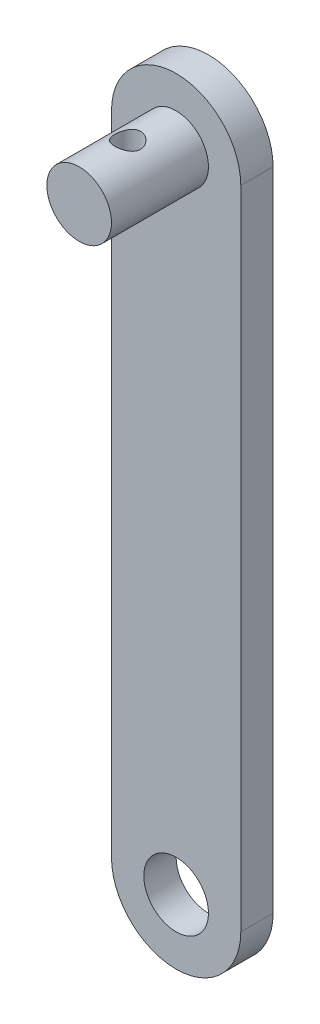
SolidWorks part; units mm, degrees
ref_plane "Front Plane" through (0, 0, 0) normal (0, 0, 1) x (1, 0, 0)
ref_plane "Top Plane" through (0, 0, 0) normal (0, 1, 0) x (1, 0, 0)
ref_plane "Right Plane" through (0, 0, 0) normal (1, 0, 0) x (0, 0, -1)
sketch "Sketch1" plane through (0, 0, 0) normal (0, 0, 1) x (1, 0, 0)
  line L0 (-12.7, -63.5) -> (-12.7, 63.5)
  line L1 (12.7, -63.5) -> (12.7, 63.5)
  line L2 (-22.7949, 0) -> (48.0321, 0) construction
  line L3 (-65.5814, 76.2) -> (65.5814, 76.2) construction
  arc A0 (-12.7, 63.5) -> (12.7, 63.5) centre (0, 63.5) cw
  circle A1 centre (0, 63.5) radius 6.35
  circle A2 centre (0, -63.5) radius 6.35
  arc A3 (-12.7, -63.5) -> (12.7, -63.5) centre (0, -63.5) ccw
  point P2 (-12.7, 0)
  point P13 (12.7, 0)
  point P15 (0, 76.2)
  dimension "D1" = 12.7
  dimension "D3" = 12.7
  dimension "D2" = 63.5
  dimension "D4" = 12.7
extrude "Boss-Extrude1" add sketch "Sketch1" along normal blind 6.35
sketch "Sketch2" plane through (0, 0, 0) normal (0, 0, 1) x (1, 0, 0)
  circle A0 centre (0, 63.5) radius 6.35
extrude "Boss-Extrude3" add sketch "Sketch2" along normal blind 25.4
sketch "Sketch4" plane through (0, 0, 0) normal (0, 0, 1) x (1, 0, 0)
  circle A0 centre (0, -63.5) radius 6.35
  dimension "D1" = 12.7
sketch "Sketch5" plane through (0, 0, 0) normal (0, 1, 0) x (1, 0, 0)
  line L0 (0, -6.35) -> (0, -25.4) construction
  line L1 (-12.7, -6.35) -> (12.7, -6.35) construction
  line L2 (-6.35, -25.4) -> (6.35, -25.4) construction
  circle A0 centre (0, -15.875) radius 2.54
  point P2 (0, -15.875)
  dimension "D1" = 5.08
extrude "Cut-Extrude2" cut sketch "Sketch5" along normal through all
